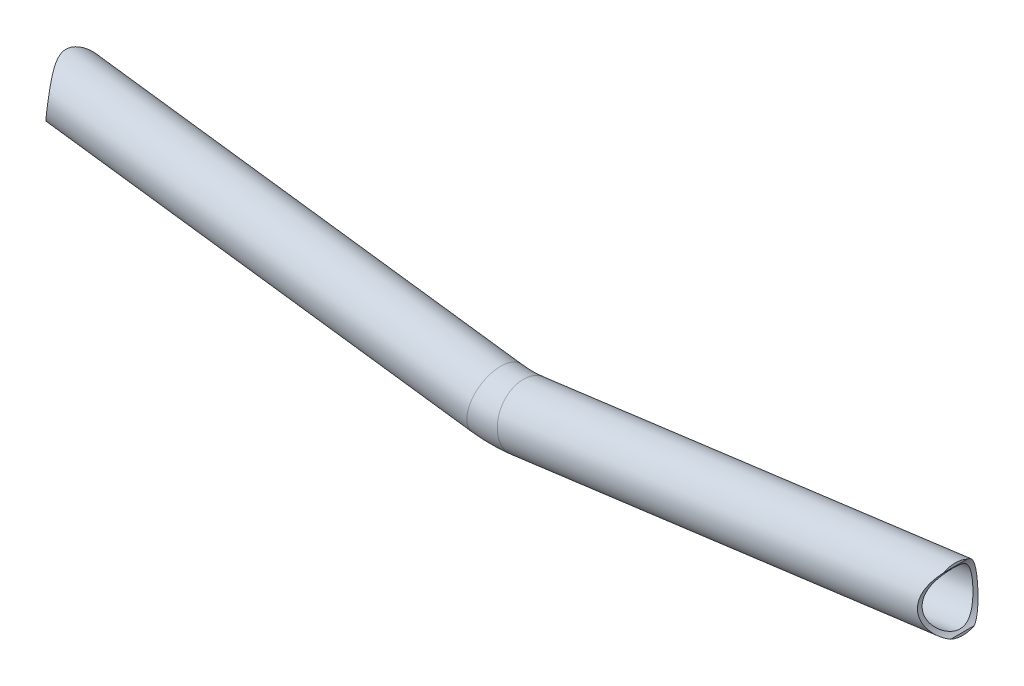
SolidWorks part; units mm, degrees
ref_plane "Plano frontal" through (0, 0, 0) normal (0, 0, 1) x (1, 0, 0)
ref_plane "Plano superior" through (0, 0, 0) normal (0, 1, 0) x (1, 0, 0)
ref_plane "Plano direito" through (0, 0, 0) normal (1, 0, 0) x (0, 0, -1)
sketch "Esboço1" plane through (0, 0, 0) normal (0, 0, 1) x (1, 0, 0)
  line L0 (-193.1294, 25.426) -> (-6.5263, 0.8592)
  line L1 (6.5263, 0.8592) -> (191.8705, 25.2602)
  line L2 (0, 0) -> (0, 108.6917) construction
  arc A0 (-6.5263, 0.8592) -> (6.5263, 0.8592) centre (0, 50.4314) ccw
  dimension "D4" = 50
  dimension "D1" = 385
  dimension "D2" = 165
  dimension "D3" = 82.5
ref_plane "Plano1" through (191.8705, 25.2602, 0) normal (0.9914, 0.1305, 0) x (0, 0, -1)
sketch "Esboço2" plane through (191.8705, 25.2602, 0) normal (0.9914, 0.1305, 0) x (0, 0, -1)
  circle A0 centre (0, 0) radius 12.75
  circle A1 centre (0, 0) radius 10.75
  dimension "D1" = 25.5
  dimension "D2" = 2
sweep "Varredura1" add profiles "Esboço2" path "Esboço1"
sketch "Esboço3" plane through (0, 0, 0) normal (0, 0, 1) x (1, 0, 0)
  circle A0 centre (-202.7131, 26.6877) radius 16
  dimension "D1" = 32
extrude "Corte-extrusão1" cut sketch "Esboço3" against normal mid plane 70
mirror "Espelhar1" about plane through (0, 0, 0) normal (1, 0, 0) of "Corte-extrusão1"
